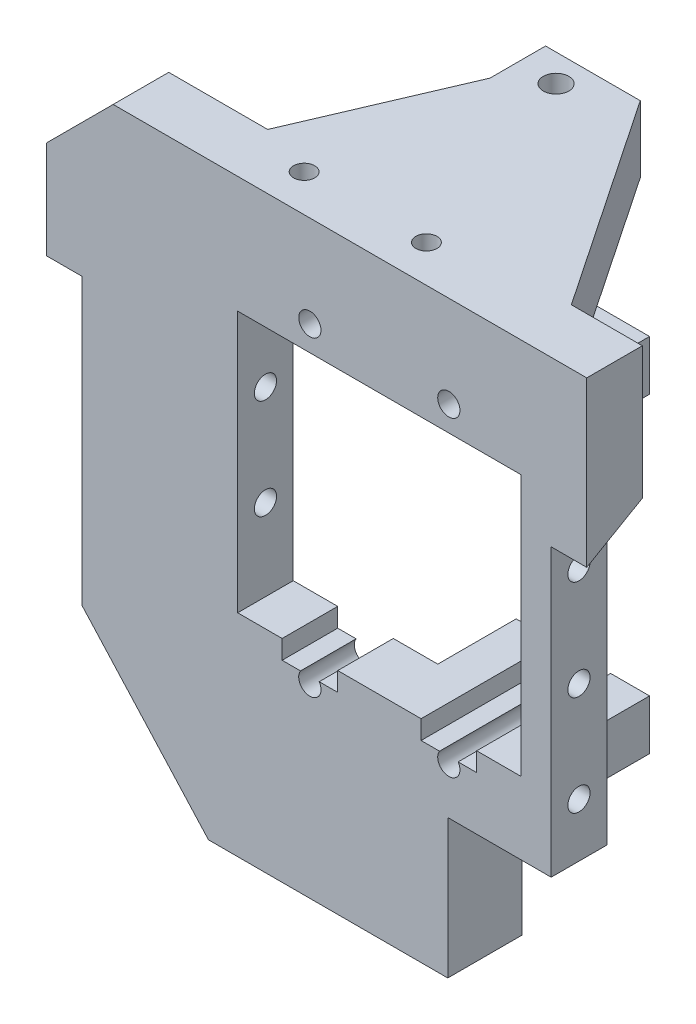
SolidWorks part; units mm, degrees
ref_plane "前视基准面" through (0, 0, 0) normal (0, 0, 1) x (1, 0, 0)
ref_plane "上视基准面" through (0, 0, 0) normal (0, 1, 0) x (1, 0, 0)
ref_plane "右视基准面" through (0, 0, 0) normal (1, 0, 0) x (0, 0, -1)
sketch "草图1" plane through (0, 0, 0) normal (0, 0, 1) x (1, 0, 0)
  line L0 (24.6404, 26.5965) -> (-17.9596, 26.5965)
  line L1 (-17.9596, 26.5965) -> (-23.9596, 20.5965)
  line L2 (-23.9596, 20.5965) -> (-23.9596, 11.8052)
  line L3 (-23.9596, 11.8052) -> (-20.7596, 11.8052)
  line L4 (-20.7596, 11.8052) -> (-20.7596, -13.8347)
  line L5 (-20.7596, -13.8347) -> (-9.3856, -26.4035)
  line L6 (-9.3856, -26.4035) -> (12.1404, -26.4035)
  line L7 (12.1404, -26.4035) -> (12.1404, -13.9035)
  line L8 (12.1404, -13.9035) -> (21.4404, -13.9035)
  line L9 (21.4404, -13.9035) -> (21.4404, 11.8351)
  line L10 (21.4404, 11.8351) -> (24.6404, 11.8351)
  line L11 (24.6404, 11.8351) -> (24.6404, 26.5965)
  line L12 (-6.7596, 16.0965) -> (18.7404, 16.0965)
  line L13 (18.7404, 16.0965) -> (18.7404, -7.4035)
  line L14 (18.7404, -7.4035) -> (14.7404, -7.4035)
  line L15 (14.7404, -7.4035) -> (14.7404, -9.1035)
  line L16 (14.7404, -9.1035) -> (9.7404, -9.1035) construction
  line L17 (9.7404, -9.1035) -> (9.7404, -7.4035)
  line L18 (9.7404, -7.4035) -> (2.2404, -7.4035)
  line L19 (2.2404, -7.4035) -> (2.2404, -9.1035)
  line L20 (2.2404, -9.1035) -> (-2.7596, -9.1035) construction
  line L21 (-2.7596, -9.1035) -> (-2.7596, -7.4035)
  line L22 (-2.7596, -7.4035) -> (-6.7596, -7.4035)
  line L23 (-6.7596, -7.4035) -> (-6.7596, 16.0965)
  line L24 (-0.2653, 18.3465) -> (12.2347, 18.3465) construction
  line L25 (-0.2653, -9.6535) -> (12.2347, -9.6535) construction
  line L26 (-0.2653, -9.6535) -> (-0.2596, -9.1035) construction
  line L27 (-2.7596, -9.1035) -> (-1.1053, -9.1035)
  line L28 (0.5747, -9.1035) -> (2.2404, -9.1035)
  line L29 (9.7404, -9.1035) -> (11.3995, -9.1035)
  line L30 (13.0699, -9.1035) -> (14.7404, -9.1035)
  circle A0 centre (12.2347, 18.3465) radius 1
  circle A1 centre (12.2347, -9.6535) radius 1 construction
  circle A2 centre (-0.2653, -9.6535) radius 1.004 construction
  circle A3 centre (-0.2653, 18.3465) radius 1
  circle A4 centre (12.2347, 18.3465) radius 1
  arc A5 (-1.1053, -9.1035) -> (0.5747, -9.1035) centre (-0.2653, -9.6535) ccw
  arc A6 (11.3995, -9.1035) -> (13.0699, -9.1035) centre (12.2347, -9.6535) ccw
  dimension "D1" = 28
  dimension "D2" = 0.55
  dimension "D3" = 5
  dimension "D4" = 7.5
  dimension "D5" = 4
  dimension "D6" = 1.7
  dimension "D7" = 23.5
  dimension "D8" = 2.7
  dimension "D9" = 14
  dimension "D10" = 10.5
  dimension "D11" = 19
  dimension "D12" = 3.2
  dimension "D13" = 9.3
  dimension "D14" = 12.5
extrude "凸台-拉伸1" add sketch "草图1" along normal blind 5 contours L10 L11 L0 L1 L2 L3 L4 L5 L6 L7 L8 L9 A6 L29 L17 L18 L19 L28 A5 L27 L21 L22 L23 L12 L13 L14 L15 L30 A3 A0
sketch "草图2" plane through (0, 0, 0) normal (0, 0, -1) x (-1, 0, 0)
  line L0 (-18.7404, -7.4035) -> (-14.7404, -7.4035) construction
  line L1 (-18.2404, -7.4035) -> (-6.2404, -7.4035) construction
  line L2 (-18.2404, -7.4035) -> (-18.2404, -11.9035)
  line L3 (-18.2404, -11.9035) -> (-6.2404, -11.9035)
  line L4 (-6.2404, -7.4035) -> (-6.2404, -11.9035)
  line L5 (-14.7404, -7.4035) -> (-14.7404, -9.1035) construction
  line L6 (-9.7404, -9.1035) -> (-9.7404, -7.4035) construction
  line L7 (-13.0699, -9.1035) -> (-14.7404, -9.1035)
  line L8 (-14.7404, -9.1035) -> (-14.7404, -7.4035)
  line L9 (-11.3995, -9.1035) -> (-9.7404, -9.1035)
  line L10 (-9.7404, -9.1035) -> (-9.7404, -7.4035)
  line L11 (-9.7404, -7.4035) -> (-6.2404, -7.4035)
  line L12 (-18.2404, -7.4035) -> (-14.7404, -7.4035)
  line L13 (6.7596, 16.0965) -> (-18.7404, 16.0965) construction
  line L14 (-18.2404, 16.0965) -> (-6.2404, 16.0965)
  line L15 (-18.2404, 16.0965) -> (-18.2404, 20.5965)
  line L16 (-18.2404, 20.5965) -> (-6.2404, 20.5965)
  line L17 (-6.2404, 16.0965) -> (-6.2404, 20.5965)
  arc A0 (-13.0699, -9.1035) -> (-11.3995, -9.1035) centre (-12.2347, -9.6535) ccw
  circle A1 centre (-12.2347, 18.3465) radius 1
  dimension "D1" = 3.5
  dimension "D2" = 3.5
  dimension "D3" = 4.5
extrude "凸台-拉伸2" add sketch "草图2" along normal blind 7.05
sketch "草图3" plane through (0, 0, 0) normal (0, 0, -1) x (-1, 0, 0)
  line L1 (9.3856, -26.4035) -> (-12.1404, -26.4035)
  line L2 (9.3856, -26.4035) -> (9.3856, -13.9035)
  line L3 (9.3856, -13.9035) -> (-12.1404, -13.9035)
  line L4 (-12.1404, -26.4035) -> (-12.1404, -13.9035)
extrude "凸台-拉伸3" add sketch "草图3" along normal blind 1.68
sketch "草图4" plane through (0, -26.4035, 0) normal (0, -1, 0) x (1, 0, 0)
  line L0 (6.8774, 1.66) -> (-4.1226, 1.66) construction
  line L1 (6.8774, 1.66) -> (12.1404, 1.66) construction
  line L2 (12.1404, 5) -> (12.1404, -1.68) construction
  line L3 (-4.1226, 1.66) -> (-9.3856, 1.66) construction
  line L4 (-9.3856, 5) -> (-9.3856, 0) construction
  line L5 (-4.1226, 1.66) -> (-4.1226, -1.68) construction
  line L6 (12.1404, -1.68) -> (-9.3856, -1.68) construction
  line L7 (-4.1226, 1.66) -> (-4.1226, 5) construction
  line L8 (-9.3856, 5) -> (12.1404, 5) construction
  circle A0 centre (6.8774, 1.66) radius 0.95
  circle A1 centre (-4.1226, 1.66) radius 0.95
  dimension "D1" = 11
extrude "切除-拉伸1" cut sketch "草图4" against normal blind 5
sketch "草图5" plane through (0, 20.5965, 0) normal (0, 1, 0) x (1, 0, 0)
  line L0 (18.256, 0) -> (5.456, 19)
  line L1 (-3.0619, 19) -> (5.456, 19)
  line L2 (-3.0619, 14) -> (-3.0619, 19)
  line L3 (-3.0619, 14) -> (-9.0619, 0)
  line L4 (-9.0619, 0) -> (18.256, 0)
  circle A0 centre (0.3443, 16.5351) radius 1.15
  point P2 (0, 0)
  dimension "D1" = 3.4062
extrude "凸台-拉伸4" add sketch "草图5" along normal blind 6 contours L1 L0 L4 L3 L2
sketch "草图6" plane through (0, 26.5965, 0) normal (0, 1, 0) x (1, 0, 0)
  circle A0 centre (-4.1226, -1.66) radius 0.95
  circle A1 centre (6.8774, -1.66) radius 0.95
extrude "切除-拉伸2" cut sketch "草图6" against normal blind 5
sketch "草图7" plane through (21.4404, 0, 0) normal (1, 0, 0) x (0, 0, -1)
  line L0 (-2.5, 8.9351) -> (0, 8.9204) construction
  line L1 (-2.5, 8.9351) -> (-5, 8.9497) construction
  line L2 (-2.5, 8.9351) -> (-2.5, -0.0664) construction
  line L3 (-2.5, -0.0664) -> (-2.5, -9.0664) construction
  line L4 (-5, 11.8351) -> (0, 11.8351)
  line L5 (-2.5, 8.9351) -> (-2.5, 11.8351) construction
  circle A0 centre (-2.5, 8.9351) radius 1
  circle A1 centre (-2.5, -0.0664) radius 1
  circle A2 centre (-2.5, -9.0664) radius 1
extrude "切除-拉伸3" cut sketch "草图7" against normal blind 100 contours A0 | A1
sketch "草图9" plane through (21.4404, 0, 0) normal (1, 0, 0) x (0, 0, -1)
  line L0 (-2.5, -0.0664) -> (-2.5, -9.0649) construction
  circle A0 centre (-2.5, -9.0649) radius 1
extrude "切除-拉伸4" cut sketch "草图9" against normal blind 3
sketch "草图10" plane through (-20.7596, 0, 0) normal (-1, 0, 0) x (0, 0, 1)
  line L0 (2.5, -0.0664) -> (2.5, -9.0649) construction
  circle A0 centre (2.5, -9.0649) radius 1
extrude "切除-拉伸5" cut sketch "草图10" against normal blind 3
sketch "草图11" plane through (24.6404, 0, 0) normal (1, 0, 0) x (0, 0, -1)
  line L0 (-5, 11.8351) -> (0, 14.7218)
  line L1 (0, 11.8351) -> (0, 26.5965) construction
  line L2 (0, 14.7218) -> (0, 11.8351)
  line L3 (0, 11.8351) -> (-5, 11.8351)
  line L4 (-5, 11.8351) -> (-5, 7.3129) construction
  dimension "D1" = 240
extrude "切除-拉伸6" cut sketch "草图11" against normal blind 3.2
sketch "草图12" plane through (-23.9596, 0, 0) normal (-1, 0, 0) x (0, 0, 1)
  line L0 (5, 11.8052) -> (0, 11.8052)
  line L1 (0, 11.8052) -> (0, 14.6919)
  line L2 (0, 20.5965) -> (0, 11.8052) construction
  line L3 (0, 14.6919) -> (5, 11.8052)
  line L4 (5, 11.8052) -> (5, 8.6778) construction
  dimension "D1" = 240
extrude "切除-拉伸7" cut sketch "草图12" against normal blind 3.2
